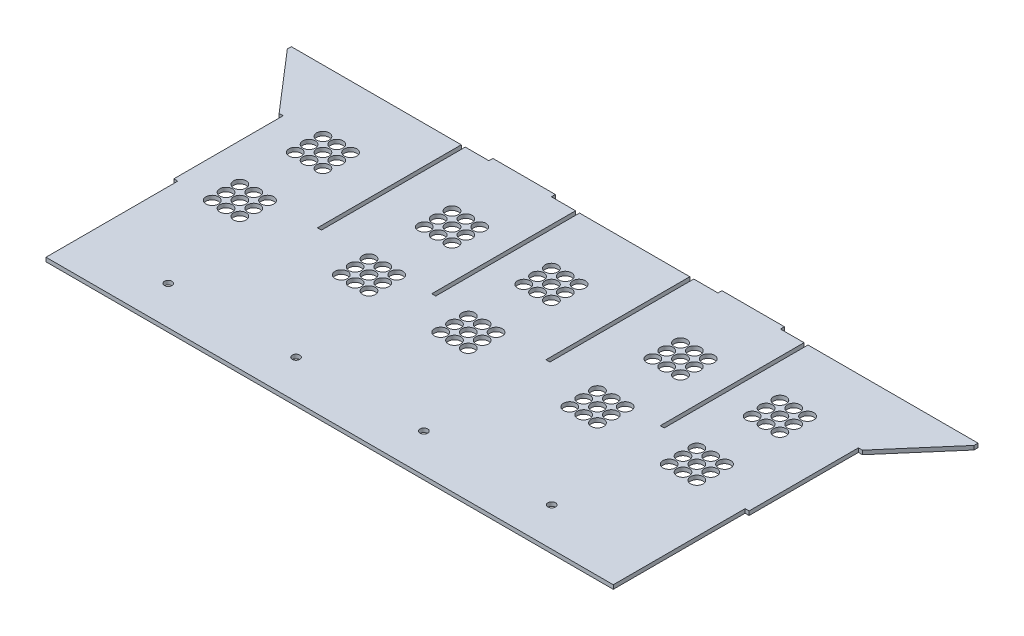
SolidWorks part; units mm, degrees
material "6061-T6 (SS)"
ref_plane "X-Y Datum" through (0, 0, 0) normal (0, 0, 1) x (1, 0, 0)
ref_plane "X-Z Datum" through (0, 0, 0) normal (0, 1, 0) x (1, 0, 0)
ref_plane "Y-Z Datum" through (0, 0, 0) normal (1, 0, 0) x (0, 0, -1)
sketch "Sketch1" plane through (0, 0, 0) normal (0, 0, 1) x (1, 0, 0)
  line L1 (-228.601, -1.5875) -> (228.601, -1.5875)
  line L2 (-228.601, -1.5875) -> (-228.601, 1.5875)
  line L3 (-228.601, 1.5875) -> (228.601, 1.5875)
  line L4 (228.601, -1.5875) -> (228.601, 1.5875)
  line L5 (-228.601, -1.5875) -> (228.601, 1.5875) construction
  line L6 (-228.601, 1.5875) -> (228.601, -1.5875) construction
  point P0 (0, 0)
  dimension "D1" = 3.175
  dimension "D2" = 457.202
extrude "Boss-Extrude1" add sketch "Sketch1" along normal blind 242.425
sketch "Sketch2" plane through (0, 1.5875, 0) normal (0, 1, 0) x (1, 0, 0)
  line L0 (228.601, 0) -> (225.426, 0)
  line L1 (228.601, 0) -> (-228.601, 0) construction
  line L2 (225.426, 0) -> (137.796, 0)
  line L3 (137.796, 0) -> (134.621, 0)
  line L10 (134.621, 0) -> (137.796, 0)
  line L11 (134.621, 0) -> (134.621, -114.3)
  line L12 (134.621, -114.3) -> (137.796, -114.3)
  line L13 (137.796, 0) -> (137.796, -114.3)
  line M2 (228.601, 0) -> (-228.601, 0)
  dimension "D1" = 87.63
  dimension "D2" = 3.175
  dimension "D3" = 114.3
  dimension "D4" = 3.175
extrude "Cut-Extrude1" cut sketch "Sketch2" against normal through all contours L13 L11 L12 M2
pattern_linear "LPattern1" count 4 spacing 90.807 along (-1, 0, 0) of "Cut-Extrude1"
sketch "Sketch4" plane through (0, -1.5875, 0) normal (0, -1, 0) x (1, 0, 0)
  line L0 (-228.601, 0) -> (-272.876, 0)
  line L2 (-228.601, 242.425) -> (-228.601, 0) construction
  line L3 (-228.601, 50.8) -> (-228.601, 0)
  line L4 (-272.876, 0) -> (-272.876, 3.175)
  line L6 (-228.601, 50.8) -> (-231.776, 50.8)
  line L7 (-231.776, 50.8) -> (-272.876, 3.175)
  dimension "D1" = 44.275
  dimension "D2" = 50.8
  dimension "D3" = 3.175
  dimension "D4" = 3.175
extrude "Boss-Extrude3" add sketch "Sketch4" against normal blind 3.175
mirror "Mirror1" about plane through (0, 0, 0) normal (1, 0, 0) of "Boss-Extrude3"
sketch "Sketch5" plane through (0, -1.5875, 0) normal (0, -1, 0) x (1, 0, 0)
  line L1 (-228.601, 242.425) -> (-225.426, 242.425)
  line L2 (-228.601, 242.425) -> (-228.601, 137.65)
  line L3 (-228.601, 137.65) -> (-225.426, 137.65)
  line L4 (-225.426, 242.425) -> (-225.426, 137.65)
  dimension "D1" = 3.175
  dimension "D2" = 104.775
extrude "Cut-Extrude2" cut sketch "Sketch5" against normal blind 3.175
mirror "Mirror2" about plane through (0, 0, 0) normal (1, 0, 0) of "Cut-Extrude2"
sketch "Sketch32" plane through (0, -1.5875, 0) normal (0, -1, 0) x (1, 0, 0)
  circle A0 centre (145.9714, 211.88) radius 3
extrude "Cut-Extrude9" cut sketch "Sketch32" against normal through all
pattern_linear "LPattern24" count 4 spacing 101.6 along (-1, 0, 0) of "Cut-Extrude9"
sketch "Sketch34" plane through (0, 1.5875, 0) normal (0, 1, 0) x (1, 0, 0)
  circle A0 centre (-198.5154, -49.2567) radius 5 construction
  circle A1 centre (-198.5154, -49.2567) radius 5
  circle A2 centre (-198.5154, -115.2567) radius 5 construction
  circle A3 centre (-198.5154, -115.2567) radius 5
extrude "Cut-Extrude10" cut sketch "Sketch34" against normal through all
pattern_linear "LPattern25" count 3 spacing 11 along (1, 0, 0) of "Cut-Extrude10"
pattern_linear "LPattern26" count 3 spacing 11 along (0, 0, 1) of "LPattern25", "Cut-Extrude10"
pattern_linear "LPattern27" count 3 spacing 181.6 along (1, 0, 0) of "LPattern26", "Cut-Extrude10", "LPattern25"
sketch "Sketch35" plane through (0, 1.5875, 0) normal (0, 1, 0) x (1, 0, 0)
  circle A0 centre (107.7014, -115.2567) radius 5 construction
  circle A1 centre (107.7014, -49.2567) radius 5 construction
  circle A2 centre (107.7014, -115.2567) radius 5
  circle A3 centre (107.7014, -49.2567) radius 5
extrude "Cut-Extrude11" cut sketch "Sketch35" against normal through all
pattern_linear "LPattern28" count 3 spacing 11 along (-1, 0, 0) of "Cut-Extrude11"
pattern_linear "LPattern29" count 3 spacing 11 along (0, 0, 1) of "LPattern28", "Cut-Extrude11"
pattern_linear "LPattern30" count 2 spacing 181.6 along (-1, 0, 0) of "LPattern29", "Cut-Extrude11", "LPattern28"
sketch "Sketch36" plane through (0, 0, 0) normal (0, 0, -1) x (-1, 0, 0)
  line L1 (66.1907, 1.5875) -> (115.8495, 1.5875)
  line L2 (66.1907, 1.5875) -> (66.1907, -1.5875)
  line L3 (66.1907, -1.5875) -> (115.8495, -1.5875)
  line L4 (115.8495, 1.5875) -> (115.8495, -1.5875)
  line L5 (-115.8495, 1.5875) -> (-66.1907, 1.5875)
  line L6 (-115.8495, 1.5875) -> (-115.8495, -1.5875)
  line L7 (-115.8495, -1.5875) -> (-66.1907, -1.5875)
  line L8 (-66.1907, 1.5875) -> (-66.1907, -1.5875)
extrude "Boss-Extrude4" add sketch "Sketch36" along normal blind 3.175
